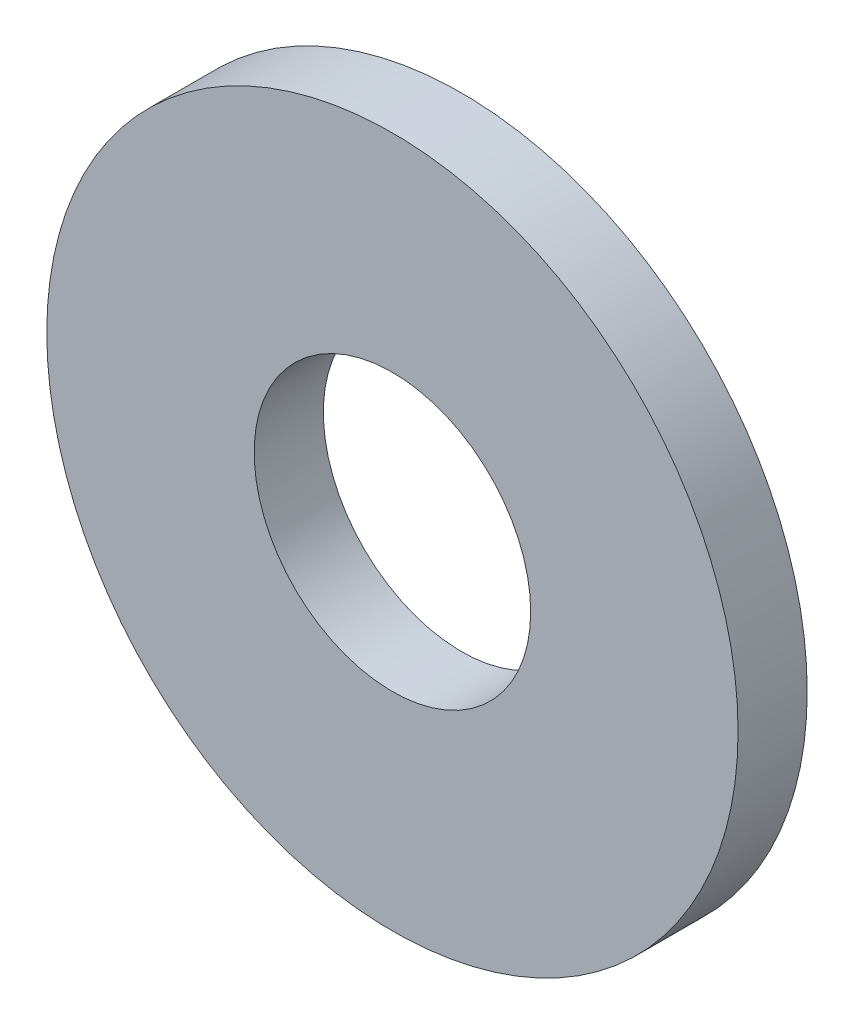
SolidWorks part; units mm, degrees
ref_plane "Piano frontale" through (0, 0, 0) normal (0, 0, 1) x (1, 0, 0)
ref_plane "Piano superiore" through (0, 0, 0) normal (0, 1, 0) x (1, 0, 0)
ref_plane "Piano destro" through (0, 0, 0) normal (1, 0, 0) x (0, 0, -1)
sketch "Schizzo1" plane through (0, 0, 0) normal (0, 0, 1) x (1, 0, 0)
  circle A0 centre (0, 0) radius 10
  circle A1 centre (0, 0) radius 25
  dimension "D1" = 50
  dimension "D2" = 20
extrude "Estrusione-Estrusione1" add sketch "Schizzo1" along normal blind 5
